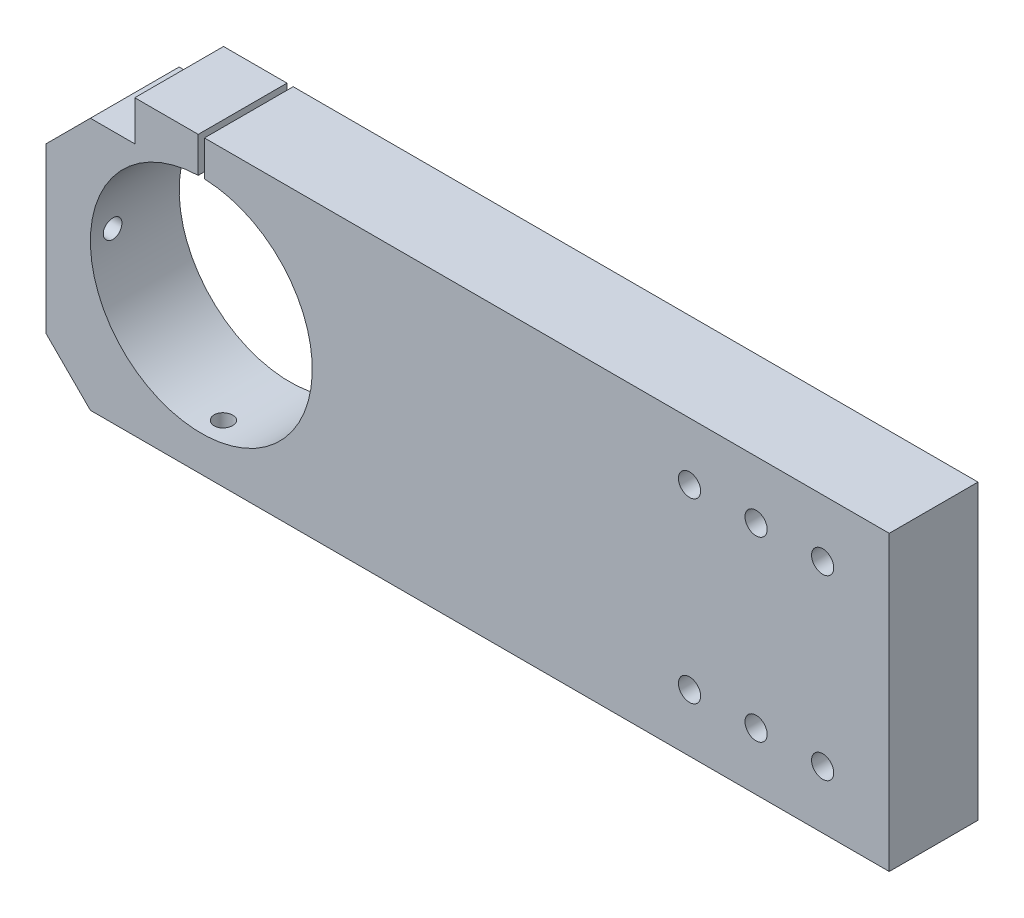
SolidWorks part; units mm, degrees
material "SKD11淬火HRC56-60"
ref_plane "前基準面" through (0, 0, 0) normal (0, 0, 1) x (1, 0, 0)
ref_plane "上基準面" through (0, 0, 0) normal (0, 1, 0) x (1, 0, 0)
ref_plane "右基準面" through (0, 0, 0) normal (1, 0, 0) x (0, 0, -1)
sketch "草图1" plane through (0, 0, 0) normal (0, 0, 1) x (1, 0, 0)
  line L1 (0, 0) -> (190, 0)
  line L2 (0, 0) -> (0, 66)
  line L3 (0, 66) -> (190, 66)
  line L4 (190, 0) -> (190, 66)
  dimension "D1" = 190
  dimension "D2" = 66
extrude "凸台-拉伸1" add sketch "草图1" along normal blind 20
sketch "草图2" plane through (0, 0, 0) normal (0, 0, -1) x (-1, 0, 0)
  line L0 (0, 33) -> (-126.3972, 33) construction
  line L1 (0, 66) -> (0, 0) construction
  line L2 (0, 66) -> (0, 0) construction
  circle A0 centre (-35, 33) radius 25
  dimension "D1" = 50
  dimension "D2" = 35
extrude "切除-拉伸1" cut sketch "草图2" against normal through all
sketch "草图3" plane through (0, 0, 0) normal (0, 0, -1) x (-1, 0, 0)
  line L1 (0, 66) -> (-20, 66)
  line L2 (0, 66) -> (0, 57)
  line L3 (0, 57) -> (-20, 57)
  line L4 (-20, 66) -> (-20, 57)
  dimension "D1" = 9
  dimension "D2" = 20
extrude "切除-拉伸2" cut sketch "草图3" against normal through all
sketch "草图4" plane through (0, 0, 0) normal (0, 0, -1) x (-1, 0, 0)
  line L0 (-190, 66) -> (-20, 66) construction
  line L1 (-34.3, 66) -> (-35.7, 66)
  line L2 (-34.3, 66) -> (-34.3, 49.0659)
  line L3 (-34.3, 49.0659) -> (-35.7, 49.0659)
  line L4 (-35.7, 66) -> (-35.7, 49.0659)
  line L5 (-35, 8) -> (-35, 80.0572) construction
  circle A0 centre (-35, 33) radius 25 construction
  dimension "D1" = 1.4
extrude "切除-拉伸3" cut sketch "草图4" against normal through all
chamfer "倒角1" distance 10 angle 45 1 edges at (0, 57, 10)
sketch "草图5" plane through (20, 0, 0) normal (-1, 0, 0) x (0, 0, 1)
  line L0 (10, 66) -> (10, 57) construction
  line L1 (20, 66) -> (0, 66) construction
  line L2 (20, 57) -> (0, 57) construction
  circle A0 centre (15, 61.5) radius 2.25
  circle A1 centre (5, 61.5) radius 2.25
  dimension "D1" = 10
  dimension "D2" = 4.5
  dimension "D3" = 4.5
extrude "切除-拉伸4" cut sketch "草图5" against normal up to surface (14.3 mm away) up to face at (34.3, 61.9951, 10)
hole_wizard "M4 螺纹孔1" positions "草图8" profile "草图7" tap size "M4" standard "ISO"
sketch "草图8" plane through (35.7, 0, 0) normal (-1, 0, 0) x (0, 0, 1)
  point P0 (15, 61.5)
  point P1 (5, 61.5)
sketch "草图7" plane through (35.7, 61.5, 15) normal (0, 1, 0) x (0, 0, 1)
  line L0 (0, 0) -> (0, 11.0914)
  line L1 (0, 11.0914) -> (1.65, 10.1)
  line L2 (1.65, 10.1) -> (1.65, 0)
  line L5 (1.65, 0) -> (0, 0)
  line L10 (0, 11.0914) -> (-1.65, 10.1) construction
  line L11 (0, -6.35) -> (0, 107.95) construction
  dimension "螺纹孔钻头直径" = 3.3
  dimension "螺纹孔钻头深度" = 10.1
  dimension "导头角度" = 118
cosmetic thread "孔螺蚊线1" parameters "D1"=8, "D2"=4
cosmetic thread "孔螺蚊线2" parameters "D1"=8, "D2"=4
hole_wizard "M5 螺纹孔1" positions "草图10" profile "草图11" tap size "M5" standard "ISO"
sketch "草图10" plane through (0, 0, 0) normal (-1, 0, 0) x (0, 0, 1)
  line L1 (20, 0) -> (0, 0) construction
  line L2 (20, 47) -> (20, 0) construction
  point P0 (15, 33)
  dimension "D1" = 5
  dimension "D2" = 33
sketch "草图11" plane through (0, 33, 15) normal (0, 1, 0) x (0, 0, 1)
  line L0 (0, 0) -> (0, 10)
  line L1 (0, 10) -> (2.1, 10)
  line L2 (2.1, 10) -> (2.1, 0)
  line L5 (2.1, 0) -> (0, 0)
  line L11 (0, -6.35) -> (0, 107.95) construction
  dimension "通孔螺纹孔钻头直径" = 4.2
  dimension "通孔螺纹孔钻头深度" = 10
cosmetic thread "孔螺蚊线3" parameters "D2"=5
hole_wizard "M5 螺纹孔2" positions "草图13" profile "草图12" tap size "M5" standard "ISO"
sketch "草图13" plane through (0, 0, 0) normal (0, -1, 0) x (1, 0, 0)
  line L0 (0, 20) -> (0, 0) construction
  line L2 (0, 20) -> (190, 20) construction
  point P0 (35, 15)
  dimension "D1" = 35
  dimension "D2" = 5
sketch "草图12" plane through (35, 0, 15) normal (1, 0, 0) x (0, 0, -1)
  line L0 (0, 0) -> (0, 13.6618)
  line L1 (0, 13.6618) -> (2.1, 12.4)
  line L2 (2.1, 12.4) -> (2.1, 0)
  line L5 (2.1, 0) -> (0, 0)
  line L10 (0, 13.6618) -> (-2.1, 12.4) construction
  line L11 (0, -6.35) -> (0, 107.95) construction
  dimension "螺纹孔钻头直径" = 4.2
  dimension "螺纹孔钻头深度" = 12.4
  dimension "导头角度" = 118
cosmetic thread "孔螺蚊线4" parameters "D1"=8.0884, "D2"=5
chamfer "倒角2" distance 10 angle 45 1 edges at (0, 0, 10)
hole_wizard "M6 螺纹孔1" positions "草图15" profile "草图16" tap size "M6" standard "ISO" end condition through all
sketch "草图15" plane through (0, 0, 0) normal (0, 0, -1) x (-1, 0, 0)
  line L0 (-190, 33) -> (-131.4612, 33) construction
  line L1 (-190, 0) -> (-190, 66) construction
  point P0 (-175, 53)
  point P1 (-175, 13)
  dimension "D1" = 40
  dimension "D2" = 15
sketch "草图16" plane through (175, 53, 0) normal (1, 0, 0) x (0, 1, 0)
  line L0 (0, 0) -> (0, 20)
  line L1 (0, 20) -> (2.5, 20)
  line L2 (2.5, 20) -> (2.5, 0)
  line L5 (2.5, 0) -> (0, 0)
  line L11 (0, -6.35) -> (0, 107.95) construction
  dimension "通孔螺纹孔钻头直径" = 5
  dimension "通孔螺纹孔钻头深度" = 20
cosmetic thread "孔螺蚊线5" parameters "D2"=6
cosmetic thread "孔螺蚊线6" parameters "D2"=6
pattern_linear "阵列(线性)1" count 3 spacing 15 along (-1, 0, 0) of "M6 螺纹孔1"
